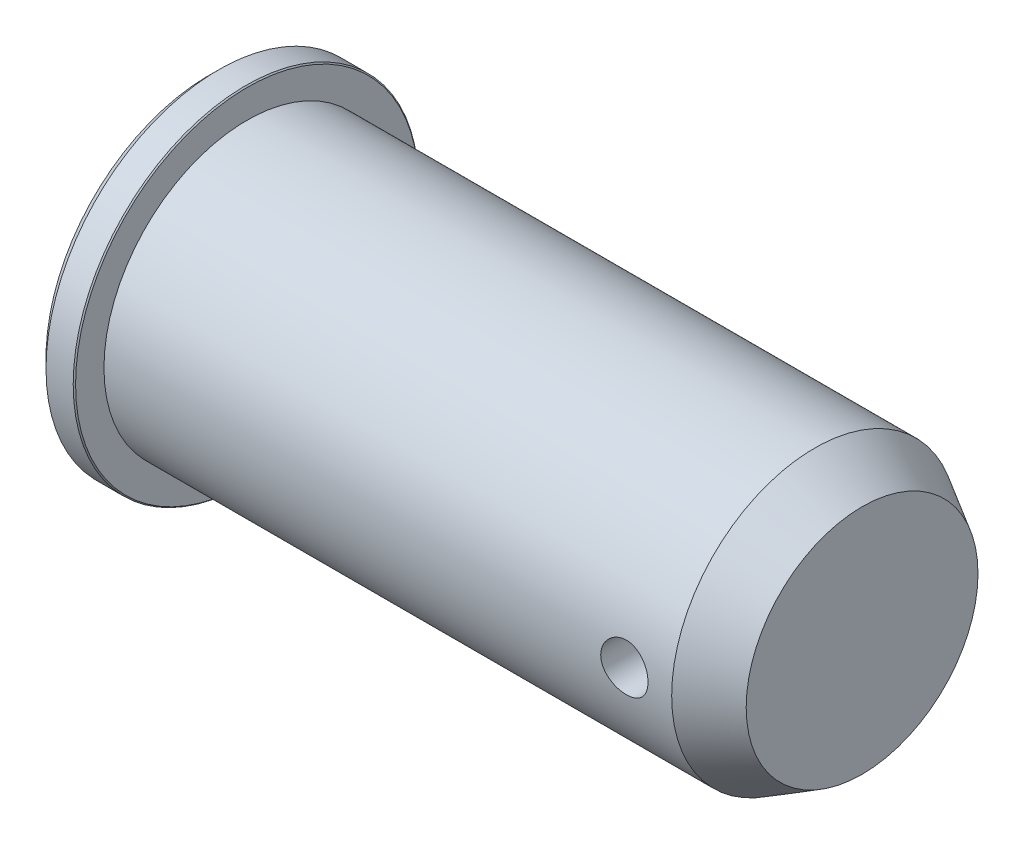
SolidWorks part; units mm, degrees
ref_plane "前视" through (0, 0, 0) normal (0, 0, 1) x (1, 0, 0)
ref_plane "上视" through (0, 0, 0) normal (0, 1, 0) x (1, 0, 0)
ref_plane "右视" through (0, 0, 0) normal (1, 0, 0) x (0, 0, -1)
sketch "草图1" plane through (0, 0, 0) normal (0, 0, 1) x (1, 0, 0)
  line L0 (0, 0) -> (0, 36.5)
  line L1 (0, 36.5) -> (8, 36.5)
  line L2 (8, 36.5) -> (8, 30.25)
  line L3 (8, 30.25) -> (128, 30.25)
  line L4 (0, 0) -> (138, 0)
  line L5 (128, 30.25) -> (138, 24.5)
  line L6 (138, 24.5) -> (138, 0)
  dimension "D1" = 36.5
  dimension "D2" = 8
  dimension "D3" = 30.25
  dimension "D4" = 120
  dimension "D5" = 24.5
  dimension "D6" = 10
revolve "旋转1" add sketch "草图1" angle 360 about L4
chamfer "倒角1" distance 2 angle 45 1 edges at (0, 0, 36.5)
ref_plane "基准面1" through (0, 0, 40) normal (0, 0, 1) x (1, 0, 0)
sketch "草图2" plane through (0, 0, 40) normal (0, 0, 1) x (1, 0, 0)
  line L0 (8, -30.25) -> (8, 30.25) construction
  circle A0 centre (118, 0) radius 5
  dimension "D1" = 10
  dimension "D2" = 110
extrude "切除-拉伸1" cut sketch "草图2" against normal through all
chamfer "倒角2" distance 0.25 angle 45 1 edges at (8, 0, 36.5)
